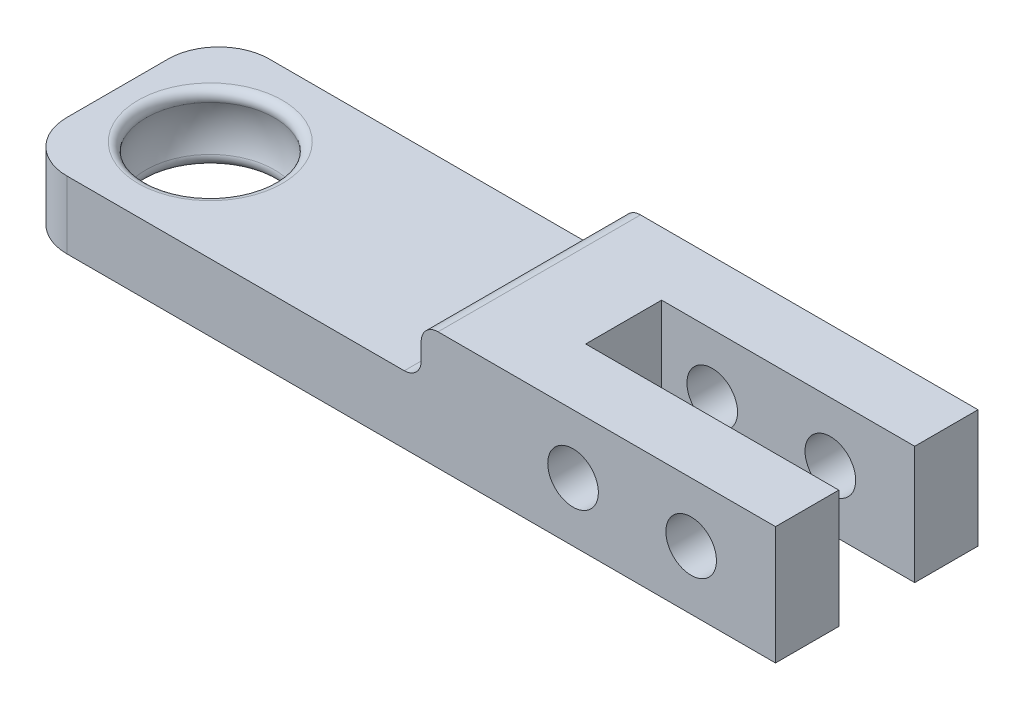
SolidWorks part; units mm, degrees
ref_plane "Front Plane" through (0, 0, 0) normal (0, 0, 1) x (1, 0, 0)
ref_plane "Top Plane" through (0, 0, 0) normal (0, 1, 0) x (1, 0, 0)
ref_plane "Right Plane" through (0, 0, 0) normal (1, 0, 0) x (0, 0, -1)
sketch "Sketch1" plane through (0, 0, 0) normal (0, 1, 0) x (1, 0, 0)
  line L1 (-22.5, 6) -> (22.5, 6)
  line L2 (-22.5, 6) -> (-22.5, -6)
  line L3 (-22.5, -6) -> (22.5, -6)
  line L4 (22.5, 6) -> (22.5, -6)
  line L5 (-22.5, 6) -> (22.5, -6) construction
  line L6 (-22.5, -6) -> (22.5, 6) construction
  point P0 (0, 0)
  dimension "D1" = 12
  dimension "D2" = 45
extrude "Boss-Extrude1" add sketch "Sketch1" along normal mid plane 4
sketch "Sketch2" plane through (0, 0, 0) normal (0, 0, 1) x (1, 0, 0)
  line L0 (-17, 2) -> (-17, -2)
  line L1 (-22.5, 2) -> (22.5, 2) construction
  line L2 (-22.5, -2) -> (22.5, -2) construction
  line L3 (-17, 2) -> (-20.5, 2)
  line L4 (-17, -2) -> (-20.5, -2)
  arc A0 (-20.5, 2) -> (-20.5, -2) centre (-17, 0) ccw
  dimension "D1" = 17
  dimension "D2" = 3.5
  dimension "D3" = 4
revolve "Cut-Revolve2" cut sketch "Sketch2" angle 360 about L0
fillet "Fillet1" radius 3 2 edges at (-22.5, 0, -6) (-22.5, 0, 6)
fillet "Fillet15" radius 0.5 2 edges at (-17, 2, 3.5) (-17, -2, 3.5)
sketch "Sketch11" plane through (22.5, 0, 0) normal (1, 0, 0) x (0, 0, -1)
  line L0 (-6, -2) -> (6, -2) construction
  line L1 (-2.25, 2) -> (2.25, 2)
  line L2 (-2.25, 2) -> (-2.25, -2)
  line L3 (-2.25, -2) -> (2.25, -2)
  line L4 (2.25, 2) -> (2.25, -2)
  line L5 (-2.25, 2) -> (2.25, -2) construction
  line L6 (-2.25, -2) -> (2.25, 2) construction
  point P0 (0, 0)
  dimension "D1" = 4.5
extrude "Cut-Extrude2" cut sketch "Sketch11" against normal blind 15 and the other way through all
sketch "Sketch13" plane through (0, 2, 0) normal (0, 1, 0) x (1, 0, 0)
  line L0 (22.5, 6) -> (-19.5, 6) construction
  line L1 (22.5, 2.25) -> (7.5, 2.25)
  line L2 (22.5, 2.25) -> (22.5, 6)
  line L3 (22.5, 6) -> (1.5, 6)
  line L4 (1.5, 2.5) -> (1.5, 6)
  line L7 (1.5, 2.5) -> (1.5, -2.5)
  line L9 (7.5, 2.25) -> (7.5, -2.25)
  line L10 (7.5, -2.25) -> (22.5, -2.25)
  line L11 (1.5, -2.5) -> (1.5, -6)
  line L12 (1.5, -6) -> (22.5, -6)
  line L13 (22.5, -2.25) -> (22.5, -6)
extrude "Boss-Extrude3" add sketch "Sketch13" along normal blind 3
sketch "Sketch14" plane through (0, 0, -6) normal (0, 0, -1) x (-1, 0, 0)
  line L0 (-22.5, 5) -> (-22.5, -2) construction
  circle A0 centre (-17.5, 1.5) radius 1.5
  circle A1 centre (-10.5, 1.5) radius 1.5
  dimension "D1" = 3
  dimension "D2" = 3
  dimension "D3" = 7
  dimension "D4" = 5
extrude "Cut-Extrude4" cut sketch "Sketch14" against normal through all
fillet "Fillet17" radius 1 2 edges at (1.5, 2, 0) (1.5, 5, 0)
